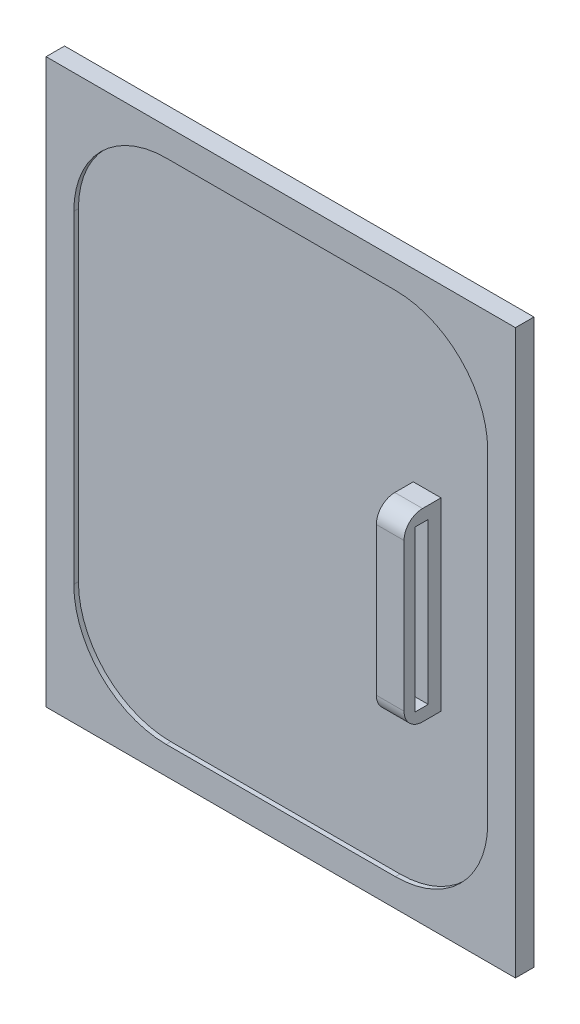
SolidWorks part; units mm, degrees
ref_plane "Front Plane" through (0, 0, 0) normal (0, 0, 1) x (1, 0, 0)
ref_plane "Top Plane" through (0, 0, 0) normal (0, 1, 0) x (1, 0, 0)
ref_plane "Right Plane" through (0, 0, 0) normal (1, 0, 0) x (0, 0, -1)
sketch "Sketch1" plane through (0, 0, 0) normal (0, 0, 1) x (1, 0, 0)
  line L1 (-127, -152.4) -> (127, -152.4)
  line L2 (-127, -152.4) -> (-127, 152.4)
  line L3 (-127, 152.4) -> (127, 152.4)
  line L4 (127, -152.4) -> (127, 152.4)
  line L5 (-127, -152.4) -> (127, 152.4) construction
  line L6 (-127, 152.4) -> (127, -152.4) construction
  point P0 (0, 0)
  dimension "D1" = 304.8
  dimension "D2" = 254
extrude "Boss-Extrude1" add sketch "Sketch1" along normal blind 10
sketch "Sketch2" plane through (0, 0, 10) normal (0, 0, 1) x (1, 0, 0)
  line L0 (127, 152.4) -> (-127, 152.4) construction
  line L1 (-62, -137.4) -> (62, -137.4)
  line L2 (-112, -87.4) -> (-112, 87.4)
  line L3 (-62, 137.4) -> (62, 137.4)
  line L4 (112, -87.4) -> (112, 87.4)
  line L5 (-112, -137.4) -> (112, 137.4) construction
  line L6 (-112, 137.4) -> (112, -137.4) construction
  line L7 (-127, 152.4) -> (-127, -152.4) construction
  arc A0 (-62, -137.4) -> (-112, -87.4) centre (-62, -87.4) cw
  arc A1 (62, -137.4) -> (112, -87.4) centre (62, -87.4) ccw
  arc A2 (62, 137.4) -> (112, 87.4) centre (62, 87.4) cw
  arc A3 (-112, 87.4) -> (-62, 137.4) centre (-62, 87.4) cw
  point P0 (0, 0)
  dimension "D3" = 50
  dimension "D1" = 15
  dimension "D2" = 15
extrude "Cut-Extrude1" cut sketch "Sketch2" against normal blind 2.5
sketch "Sketch3" plane through (0, 0, 7.5) normal (0, 0, 1) x (1, 0, 0)
  line L3 (69.2187, -50) -> (84.2187, -50)
  line L4 (69.2187, -50) -> (69.2187, 50)
  line L5 (69.2187, 50) -> (84.2187, 50)
  line L6 (84.2187, -50) -> (84.2187, 50)
  line L7 (69.2187, -50) -> (84.2187, 50) construction
  line L8 (69.2187, 50) -> (84.2187, -50) construction
  point P5 (76.7187, 0)
  dimension "D1" = 100
  dimension "D2" = 15
extrude "Boss-Extrude2" add sketch "Sketch3" along normal blind 20
sketch "Sketch4" plane through (84.2187, 0, 0) normal (1, 0, 0) x (0, 0, -1)
  line L11 (-21.611, -43.3465) -> (-14.4187, -43.3465)
  line L12 (-21.611, -43.3465) -> (-21.611, 43.3465)
  line L13 (-21.611, 43.3465) -> (-14.4187, 43.3465)
  line L14 (-14.4187, -43.3465) -> (-14.4187, 43.3465)
  line L15 (-21.611, -43.3465) -> (-14.4187, 43.3465) construction
  line L16 (-21.611, 43.3465) -> (-14.4187, -43.3465) construction
  point P0 (-18.0148, 0)
extrude "Cut-Extrude4" cut sketch "Sketch4" against normal through all both and the other way through all contours L12 L13 L14 L11
fillet "Fillet2" radius 10 2 edges at (76.7187, -50, 27.5) (76.7187, 50, 27.5)
